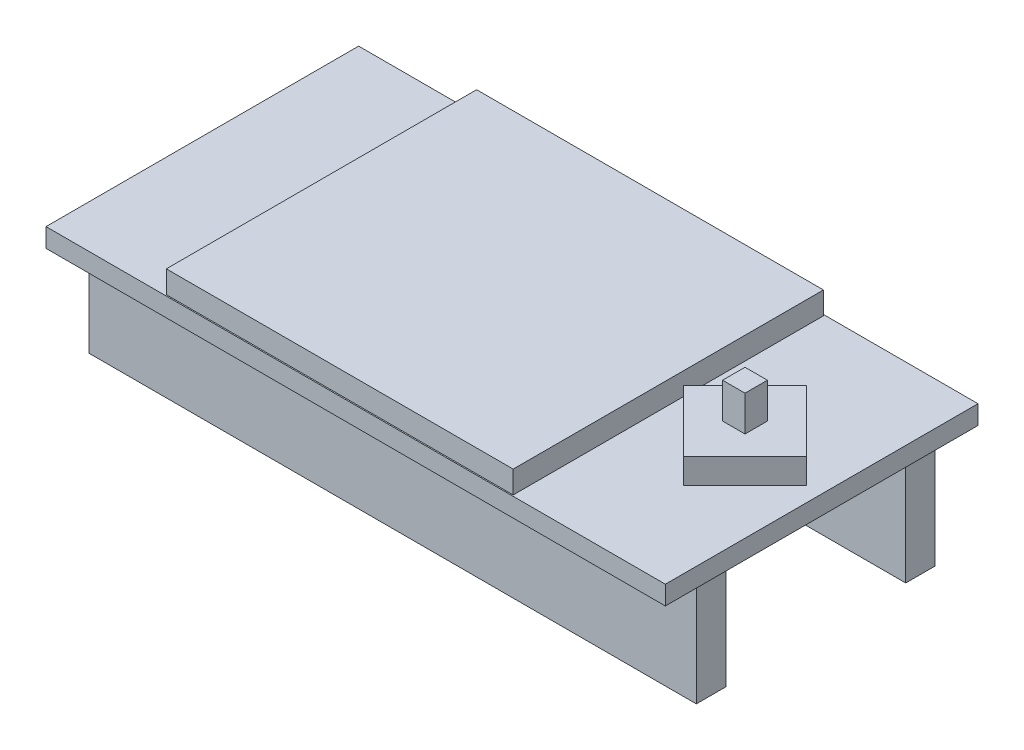
SolidWorks part; units mm, degrees
ref_plane "Front Plane" through (0, 0, 0) normal (0, 0, 1) x (1, 0, 0)
ref_plane "Top Plane" through (0, 0, 0) normal (0, 1, 0) x (1, 0, 0)
ref_plane "Right Plane" through (0, 0, 0) normal (1, 0, 0) x (0, 0, -1)
sketch "Sketch1" plane through (0, 0, 0) normal (0, 1, 0) x (1, 0, 0)
  line L0 (0, 8.875) -> (0, -8.875) construction
  line L1 (25.75, 7.625) -> (-25.75, 7.625)
  line L2 (25.75, 7.625) -> (25.75, 10.125)
  line L3 (25.75, 10.125) -> (-25.75, 10.125)
  line L4 (-25.75, 7.625) -> (-25.75, 10.125)
  line L5 (25.75, 7.625) -> (-25.75, 10.125) construction
  line L6 (25.75, 10.125) -> (-25.75, 7.625) construction
  line L7 (25.75, -10.125) -> (-25.75, -10.125)
  line L8 (25.75, -10.125) -> (25.75, -7.625)
  line L9 (25.75, -7.625) -> (-25.75, -7.625)
  line L10 (-25.75, -10.125) -> (-25.75, -7.625)
  line L11 (25.75, -10.125) -> (-25.75, -7.625) construction
  line L12 (25.75, -7.625) -> (-25.75, -10.125) construction
  point P0 (0, 8.875)
  point P5 (0, -8.875)
  dimension "D1" = 51.5
  dimension "D2" = 2.5
  dimension "D3" = 20.25
extrude "Boss-Extrude1" add sketch "Sketch1" along normal blind 9
sketch "Sketch2" plane through (0, 9, 0) normal (0, 1, 0) x (1, 0, 0)
  line L1 (26.25, -13.25) -> (-26.25, -13.25)
  line L2 (26.25, -13.25) -> (26.25, 13.25)
  line L3 (26.25, 13.25) -> (-26.25, 13.25)
  line L4 (-26.25, -13.25) -> (-26.25, 13.25)
  line L5 (26.25, -13.25) -> (-26.25, 13.25) construction
  line L6 (26.25, 13.25) -> (-26.25, -13.25) construction
  point P0 (0, 0)
  dimension "D1" = 52.5
  dimension "D2" = 26.5
extrude "Boss-Extrude2" add sketch "Sketch2" along normal blind 1.6
sketch "Sketch3" plane through (0, 10.6, 0) normal (0, 1, 0) x (1, 0, 0)
  line L0 (26.25, -13.25) -> (26.25, 13.25) construction
  line L1 (-16.15, 13.15) -> (13.25, 13.15)
  line L2 (-16.15, 13.15) -> (-16.15, -13.15)
  line L3 (-16.15, -13.15) -> (13.25, -13.15)
  line L4 (13.25, 13.15) -> (13.25, -13.15)
  line L5 (-16.15, 13.15) -> (13.25, -13.15) construction
  line L6 (-16.15, -13.15) -> (13.25, 13.15) construction
  point P0 (-1.45, 0)
  point P5 (0, 0)
  dimension "D1" = 29.4
  dimension "D2" = 26.3
  dimension "D3" = 13
extrude "Boss-Extrude3" add sketch "Sketch3" along normal blind 1.9
sketch "Sketch4" plane through (0, 10.6, 0) normal (0, 1, 0) x (1, 0, 0)
  line L0 (26.25, -13.25) -> (26.25, 13.25) construction
  line L1 (24.9826, 0) -> (19.75, -5.2326)
  line L2 (24.9826, 0) -> (19.75, 5.2326)
  line L3 (19.75, 5.2326) -> (14.5174, 0)
  line L4 (19.75, -5.2326) -> (14.5174, 0)
  line L5 (24.9826, 0) -> (14.5174, 0) construction
  line L6 (19.75, 5.2326) -> (19.75, -5.2326) construction
  point P0 (19.75, 0)
  point P7 (15.3457, 0.4037)
  point P8 (0, 0)
  dimension "D1" = 6.5
  dimension "D2" = 7.4
extrude "Boss-Extrude4" add sketch "Sketch4" along normal blind 2.1
sketch "Sketch5" plane through (0, 12.7, 0) normal (0, 1, 0) x (1, 0, 0)
  line L1 (18.8, 0.95) -> (20.7, 0.95)
  line L2 (18.8, 0.95) -> (18.8, -0.95)
  line L3 (18.8, -0.95) -> (20.7, -0.95)
  line L4 (20.7, 0.95) -> (20.7, -0.95)
  line L5 (18.8, 0.95) -> (20.7, -0.95) construction
  line L6 (18.8, -0.95) -> (20.7, 0.95) construction
  point P0 (19.75, 0)
  point P5 (0, 0)
  point P8 (0, 0)
  dimension "D1" = 1.9
extrude "Boss-Extrude5" add sketch "Sketch5" along normal blind 3
